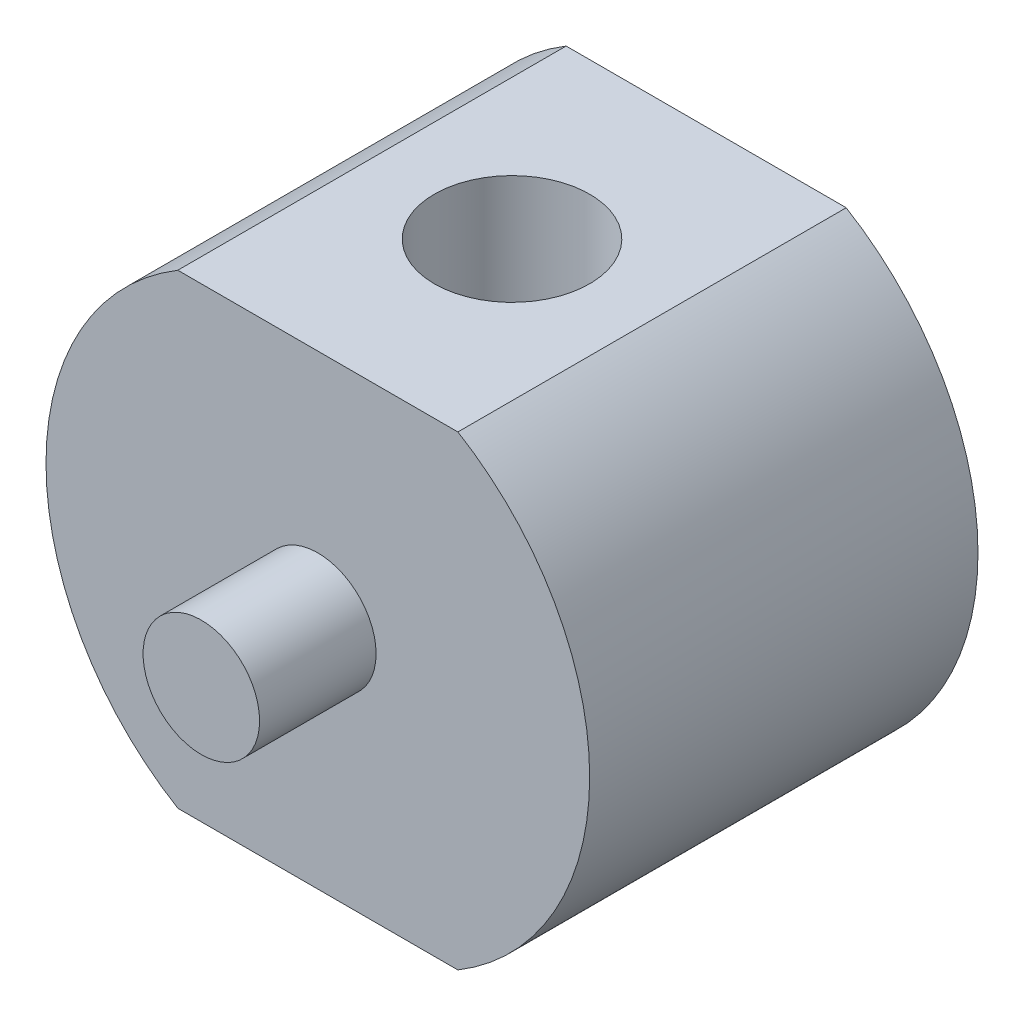
SolidWorks part; units mm, degrees
ref_plane "Plan1" through (0, 0, 0) normal (0, 0, 1) x (1, 0, 0)
ref_plane "Plan2" through (0, 0, 0) normal (0, 1, 0) x (1, 0, 0)
ref_plane "Plan3" through (0, 0, 0) normal (1, 0, 0) x (0, 0, -1)
sketch "Esquisse1" plane through (0, 0, 0) normal (0, 0, 1) x (1, 0, 0)
  line L0 (-3.6065, 5.9994) -> (3.6065, 5.9994)
  line L1 (-3.6065, -5.9994) -> (3.6065, -5.9994)
  arc A0 (-3.6065, 5.9994) -> (-3.6065, -5.9994) centre (0, 0) ccw
  arc A1 (3.6065, -5.9994) -> (3.6065, 5.9994) centre (0, 0) ccw
  dimension "D1" = 14
  dimension "D2" = 11.9989
  dimension "D3" = 5.9994
extrude "Base-Extrusion" add sketch "Esquisse1" along normal blind 10
sketch "Esquisse2" plane through (0, 0, 10) normal (0, 0, 1) x (1, 0, 0)
  circle A0 centre (0, 0) radius 1.5
  dimension "D1" = 3
extrude "Boss.-Extru.1" add sketch "Esquisse2" along normal blind 3
sketch "Esquisse3" plane through (0, 0, 0) normal (0, 0, -1) x (-1, 0, 0)
  circle A0 centre (0, 0) radius 1.5
  dimension "D1" = 3
extrude "Boss.-Extru.2" add sketch "Esquisse3" along normal blind 3
hole_wizard "Perçage1" positions "Esquisse5" profile "Esquisse4" legacy
sketch "Esquisse5" plane through (0, 5.9994, 0) normal (0, 1, 0) x (-1, 0, 0)
  line L0 (0, 8.2524) -> (0, -0.444) construction
  line L1 (-1.4694, 0) -> (1.2636, 0) construction
  line L2 (3.6065, 0) -> (-3.6065, 0) construction
  point P0 (0, 5)
  dimension "D1" = 5
sketch "Esquisse4" plane through (0, 5.9994, 5) normal (1, 0, 0) x (0, 0, 1)
  line L0 (0, 0) -> (0, 13.2006)
  line L1 (0, 13.2006) -> (2, 11.9989)
  line L2 (2, 11.9989) -> (2, 0)
  line L4 (2, 0) -> (0, 0)
  line L6 (0, 13.2006) -> (-2, 11.9989) construction
  line L7 (0, -4.2442) -> (0, 117.3081) construction
  dimension "Diamètre" = 4
  dimension "Profondeur" = 11.9989
  dimension "Angle" = 118
